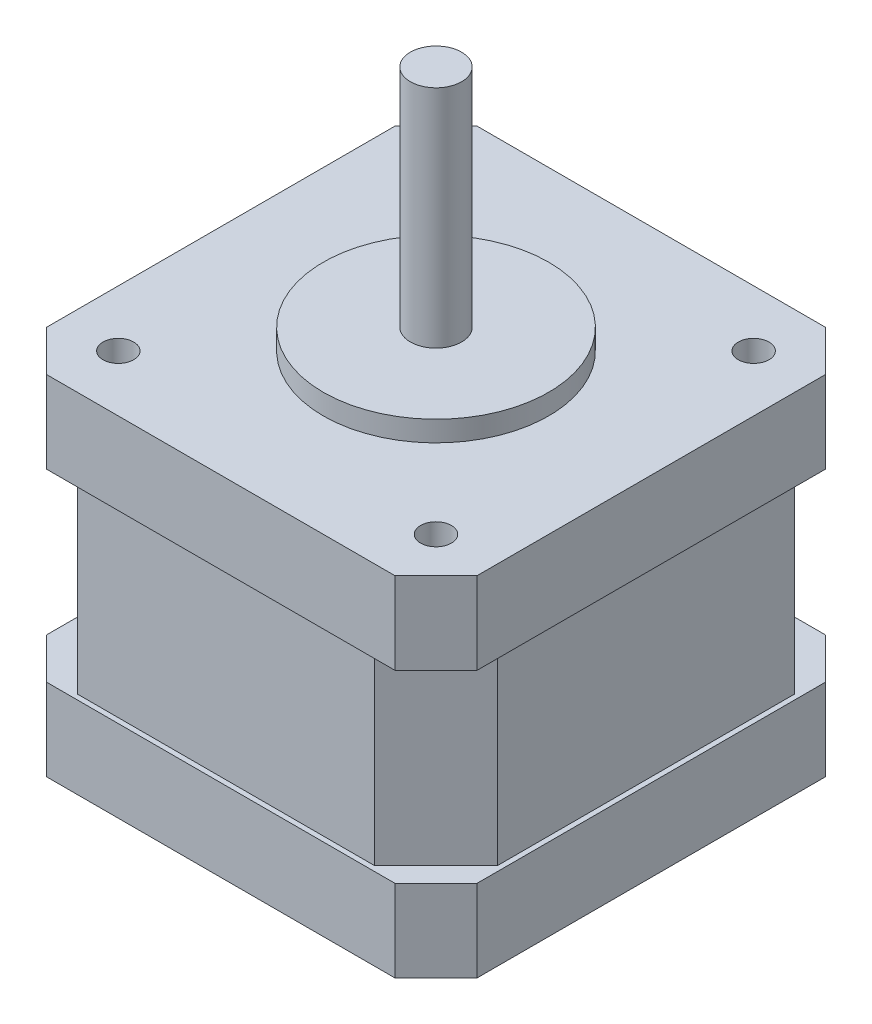
SolidWorks part; units mm, degrees
ref_plane "Front Plane" through (0, 0, 0) normal (0, 0, 1) x (1, 0, 0)
ref_plane "Top Plane" through (0, 0, 0) normal (0, 1, 0) x (1, 0, 0)
ref_plane "Right Plane" through (0, 0, 0) normal (1, 0, 0) x (0, 0, -1)
sketch "Sketch1" plane through (0, 0, 0) normal (0, 1, 0) x (1, 0, 0)
  line L0 (-21, 21) -> (21, -21) construction
  line L1 (-21, 21) -> (21, 21)
  line L2 (-21, 21) -> (-21, -21)
  line L3 (-21, -21) -> (21, -21)
  line L4 (21, 21) -> (21, -21)
  dimension "D1" = 42
extrude "Boss-Extrude1" add sketch "Sketch1" along normal blind 8
pattern_linear "LPattern2" count 2 spacing 26 along (0, -1, 0) of bodies 101
sketch "Sketch5" plane through (0, 0, 0) normal (0, -1, 0) x (1, 0, 0)
  line L8 (-20.5, 20.5) -> (-20.5, -20.5)
  line L9 (-20.5, -20.5) -> (20.5, -20.5)
  line L10 (20.5, -20.5) -> (20.5, 20.5)
  line L11 (20.5, 20.5) -> (-20.5, 20.5)
  line L12 (-20.5, 20.5) -> (-20.5, -20.5)
  line L13 (-20.5, -20.5) -> (20.5, -20.5)
  line L14 (20.5, -20.5) -> (20.5, 20.5)
  line L15 (20.5, 20.5) -> (-20.5, 20.5)
  dimension "D1" = 0.5
extrude "Boss-Extrude4" add sketch "Sketch5" along normal up to next
chamfer "Chamfer2" distance 6 angle 45 4 edges at (20.5, -9, -20.5) (20.5, -9, 20.5) (-20.5, -9, 20.5) (-20.5, -9, -20.5)
chamfer "Chamfer1" distance 4 angle 45 8 edges at (-21, 4, -21) (-21, 4, 21) (21, 4, -21) (21, 4, 21) (-21, -22, -21) (-21, -22, 21) (21, -22, -21) (21, -22, 21)
sketch "Sketch2" plane through (0, 8, 0) normal (0, 1, 0) x (1, 0, 0)
  circle A0 centre (0, 0) radius 11
  dimension "D1" = 22
extrude "Boss-Extrude2" add sketch "Sketch2" along normal blind 2
sketch "Sketch3" plane through (0, 10, 0) normal (0, 1, 0) x (1, 0, 0)
  circle A0 centre (0, 0) radius 2.5
  dimension "D1" = 5
extrude "Boss-Extrude3" add sketch "Sketch3" along normal blind 22
sketch "Sketch6" plane through (0, 8, 0) normal (0, 1, 0) x (1, 0, 0)
  line L0 (-15.5, 15.5) -> (15.5, 15.5) construction
  line L1 (15.5, 15.5) -> (15.5, -15.5) construction
  line L2 (15.5, -15.5) -> (-15.5, -15.5) construction
  line L3 (-15.5, -15.5) -> (-15.5, 15.5) construction
  line L4 (-15.5, 15.5) -> (15.5, -15.5) construction
  circle A0 centre (-15.5, 15.5) radius 1.5
  circle A1 centre (15.5, 15.5) radius 1.5
  circle A2 centre (15.5, -15.5) radius 1.5
  circle A3 centre (-15.5, -15.5) radius 1.5
  dimension "D1" = 3
  dimension "D2" = 31
extrude "Cut-Extrude1" cut sketch "Sketch6" against normal blind 7
